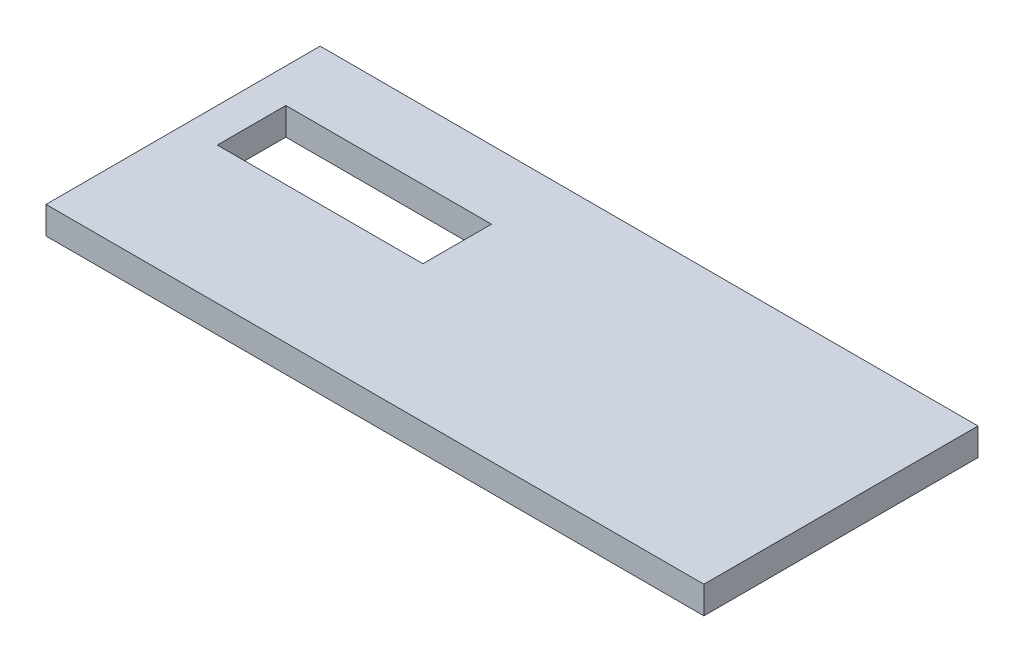
SolidWorks part; units mm, degrees
ref_plane "Front Plane" through (0, 0, 0) normal (0, 0, 1) x (1, 0, 0)
ref_plane "Top Plane" through (0, 0, 0) normal (0, 1, 0) x (1, 0, 0)
ref_plane "Right Plane" through (0, 0, 0) normal (1, 0, 0) x (0, 0, -1)
sketch "Sketch1" plane through (0, 0, 0) normal (0, 1, 0) x (1, 0, 0)
  line L1 (0, 0) -> (96, 0)
  line L2 (0, 0) -> (0, -40)
  line L3 (0, -40) -> (96, -40)
  line L4 (96, 0) -> (96, -40)
  line L5 (5, -10) -> (35, -10)
  line L6 (5, -10) -> (5, -20)
  line L7 (5, -20) -> (35, -20)
  line L8 (35, -10) -> (35, -20)
  dimension "D1" = 96
  dimension "D2" = 40
  dimension "D3" = 10
  dimension "D4" = 5
  dimension "D5" = 10
  dimension "D6" = 35
extrude "Boss-Extrude1" add sketch "Sketch1" along normal blind 4
